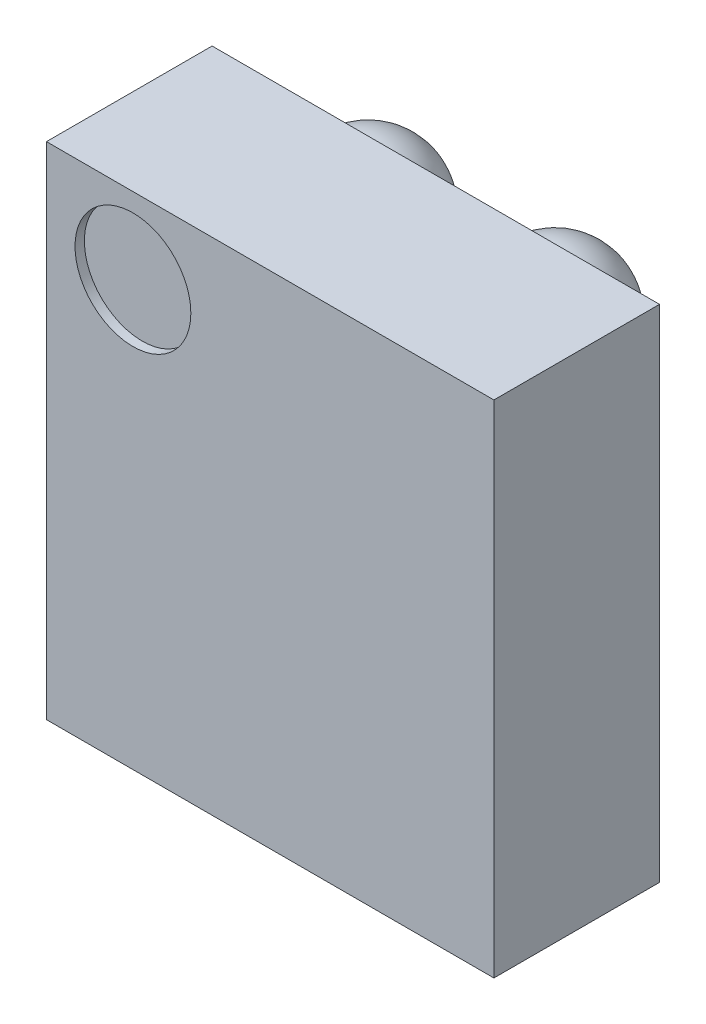
SolidWorks part; units mm, degrees
ref_plane "Front Plane" through (0, 0, 0) normal (0, 0, 1) x (1, 0, 0)
ref_plane "Top Plane" through (0, 0, 0) normal (0, 1, 0) x (1, 0, 0)
ref_plane "Right Plane" through (0, 0, 0) normal (1, 0, 0) x (0, 0, -1)
sketch "Sketch1" plane through (0, 0, 0) normal (0, 0, 1) x (1, 0, 0)
  line L1 (-0.4795, -0.5365) -> (0.4795, -0.5365)
  line L2 (-0.4795, -0.5365) -> (-0.4795, 0.5365)
  line L3 (-0.4795, 0.5365) -> (0.4795, 0.5365)
  line L4 (0.4795, -0.5365) -> (0.4795, 0.5365)
  line L5 (-0.4795, -0.5365) -> (0.4795, 0.5365) construction
  line L6 (-0.4795, 0.5365) -> (0.4795, -0.5365) construction
  point P0 (0, 0)
  dimension "D1" = 0.959
  dimension "D2" = 1.073
extrude "Boss-Extrude1" add sketch "Sketch1" along normal blind 0.355 from offset 0.19 contours L3 L4 L1 L2
sketch "Sketch2" plane through (0, 0, 0) normal (0, 1, 0) x (1, 0, 0)
  line L0 (0, 0) -> (0, -0.27)
  arc A0 (0, -0.27) -> (0, 0) centre (0, -0.135) ccw
  dimension "D1" = 0.27
revolve "Revolve1" add sketch "Sketch2" angle 360 about L0
pattern_linear "LPattern1" count 2 spacing 0.3465 along (0, 1, 0) count 2 spacing 0.2 along (1, 0, 0) skipping (0, 1), (1, 0) of "Revolve1"
pattern_linear "LPattern2" count 2 spacing 0.693 along (0, -1, 0) count 2 spacing 0.4 along (-1, 0, 0) of "LPattern1"
sketch "Sketch3" plane through (0, 0, 0.545) normal (0, 0, 1) x (1, 0, 0)
  circle A0 centre (-0.2942, 0.3729) radius 0.1241
  point P2 (-0.2942, 0.3729)
extrude "Cut-Extrude3" cut sketch "Sketch3" against normal blind 0.02 contours A0
